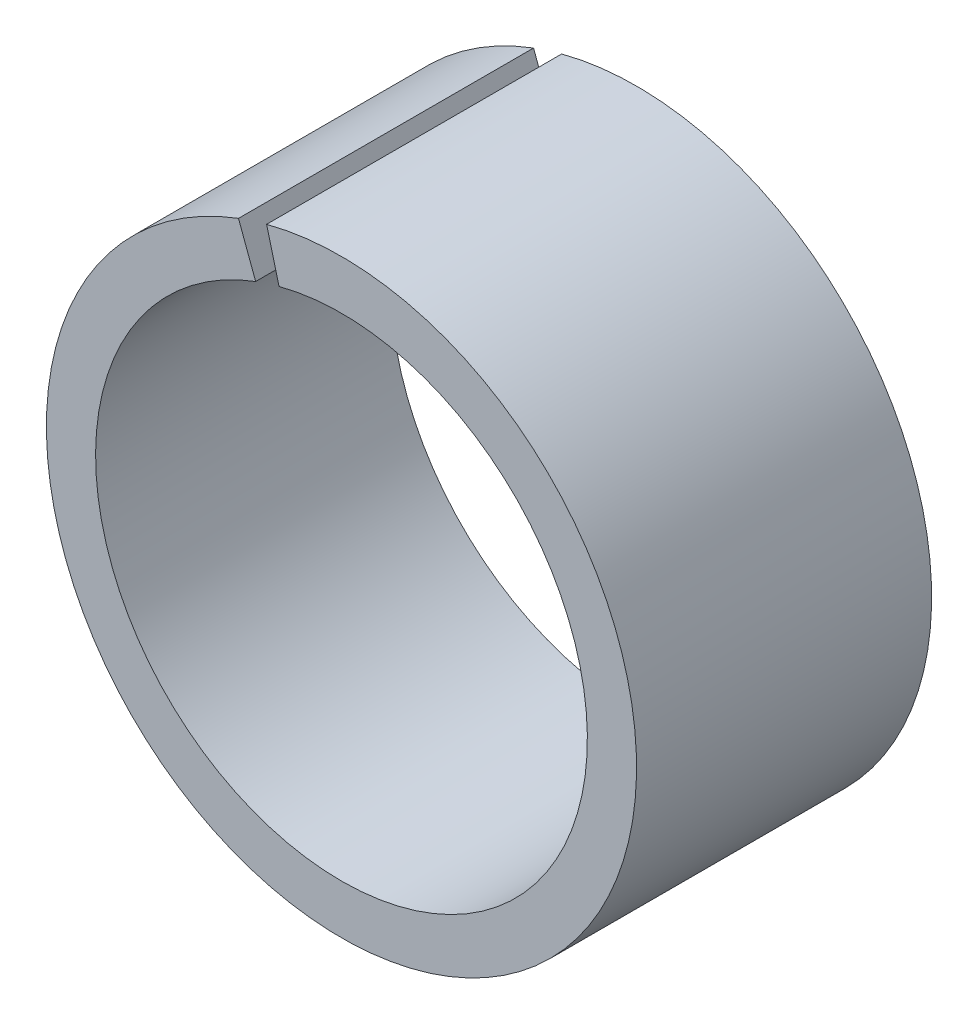
SolidWorks part; units mm, degrees
ref_plane "前视基准面" through (0, 0, 0) normal (0, 0, 1) x (1, 0, 0)
ref_plane "上视基准面" through (0, 0, 0) normal (0, 1, 0) x (1, 0, 0)
ref_plane "右视基准面" through (0, 0, 0) normal (1, 0, 0) x (0, 0, -1)
sketch "草图1" plane through (0, 0, 0) normal (0, 0, 1) x (1, 0, 0)
  circle A0 centre (0, 0) radius 6
  circle A1 centre (0, 0) radius 5
  dimension "D1" = 10
  dimension "D2" = 12
extrude "凸台-拉伸1" add sketch "草图1" along normal blind 6
sketch "草图2" plane through (0, 0, 6) normal (0, 0, 1) x (1, 0, 0)
  line L0 (0, 0) -> (-3.5798, 9.6104)
  line L1 (0, 0) -> (-2.6158, 9.9695)
  line L2 (-2.6158, 9.9695) -> (-3.5798, 9.6104)
extrude "切除-拉伸1" cut sketch "草图2" against normal blind 10
